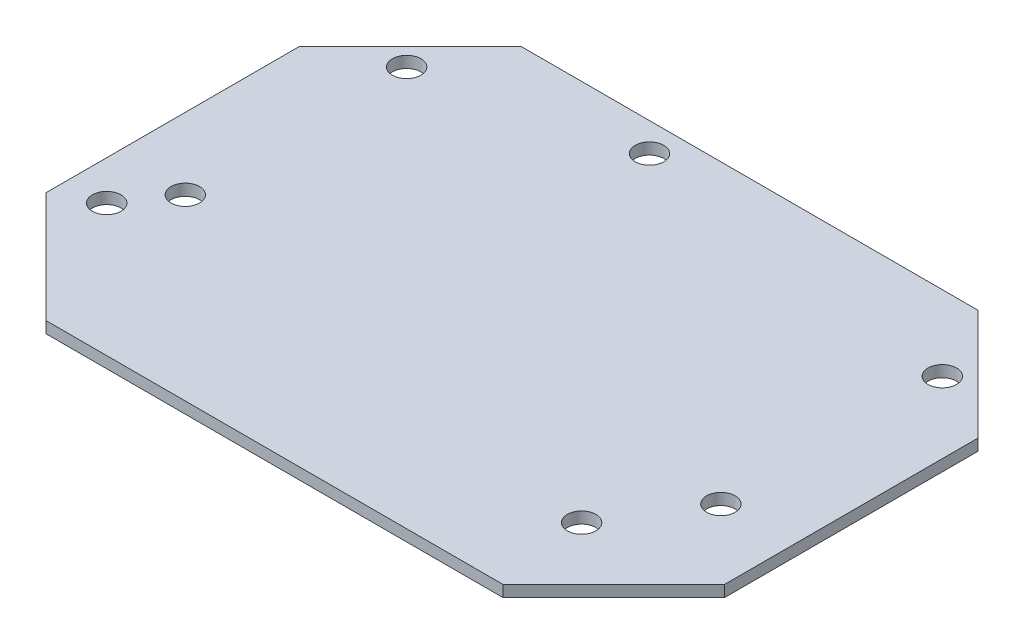
SolidWorks part; units mm, degrees
material "A-Glass Fiber"
ref_plane "Front Plane" through (0, 0, 0) normal (0, 0, 1) x (1, 0, 0)
ref_plane "Top Plane" through (0, 0, 0) normal (0, 1, 0) x (1, 0, 0)
ref_plane "Right Plane" through (0, 0, 0) normal (1, 0, 0) x (0, 0, -1)
sketch "Sketch1" plane through (0, 0, 0) normal (0, 1, 0) x (1, 0, 0)
  line L0 (0, 15.5) -> (15.5, 0)
  line L1 (15.5, 0) -> (79.5, 0)
  line L2 (0, 15.5) -> (0, 51)
  line L3 (15.5, 66.5) -> (79.5, 66.5)
  line L4 (95, 15.5) -> (95, 51)
  line L5 (0, 51) -> (15.5, 66.5)
  line L6 (95, 51) -> (79.5, 66.5)
  line L7 (95, 15.5) -> (79.5, 0)
  dimension "D1" = 66.5
  dimension "D2" = 95
  dimension "D3" = 15.5
  dimension "D4" = 135
  dimension "D5" = 135
  dimension "D6" = 135
  dimension "D7" = 15.5
  dimension "D8" = 15.5
  dimension "D9" = 15.5
extrude "Boss-Extrude1" add sketch "Sketch1" along normal blind 1.6 contours L0 L1 L7 L4 L6 L3 L5 L2
sketch "Sketch2" plane through (0, 1.6, 0) normal (0, 1, 0) x (1, 0, 0)
  line L0 (15.5, 0) -> (79.5, 0) construction
  line L1 (0, 15.5) -> (0, 51) construction
  circle A0 centre (5.5, 18.5) radius 2
  circle A1 centre (77.5, 13) radius 2
  circle A2 centre (37.5, 62.5) radius 2
  dimension "D1" = 4
  dimension "D2" = 4
  dimension "D3" = 4
  dimension "D4" = 5.5
  dimension "D5" = 18.5
  dimension "D6" = 13
  dimension "D7" = 77.5
  dimension "D8" = 62.5
  dimension "D9" = 37.5
extrude "Cut-Extrude1" cut sketch "Sketch2" against normal through all
sketch "Sketch3" plane through (0, 1.6, 0) normal (0, 1, 0) x (1, 0, 0)
  circle A0 centre (10, 56) radius 2
  circle A1 centre (85, 56) radius 2
  circle A2 centre (85, 25) radius 2
  circle A3 centre (10, 25) radius 2
  circle A4 centre (10, 56) radius 1.85 construction
  circle A5 centre (85, 56) radius 1.85 construction
  circle A6 centre (85, 25) radius 1.85 construction
  circle A7 centre (10, 25) radius 1.85 construction
  point P12 (10.15, 25)
  point P15 (19.1272, 30.0954)
  point P16 (71.4665, 25.1796)
  point P17 (79.3018, 46.7228)
  dimension "D1" = 4
  dimension "D2" = 4
  dimension "D3" = 4
  dimension "D4" = 4
extrude "Cut-Extrude2" cut sketch "Sketch3" against normal up to next
